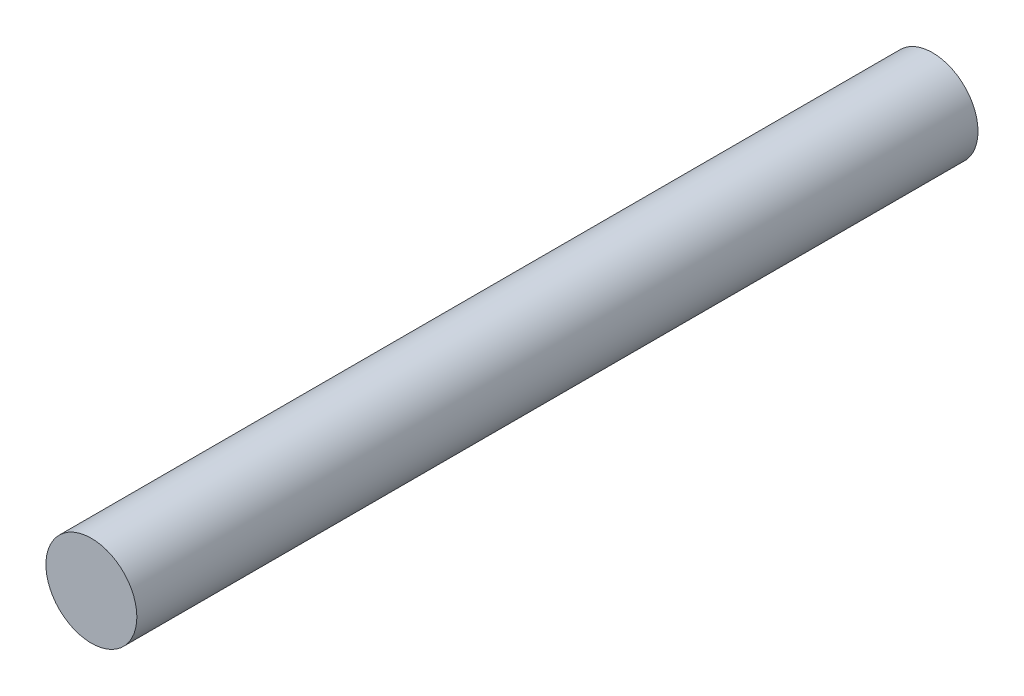
SolidWorks part; units mm, degrees
ref_plane "Front Plane" through (0, 0, 0) normal (1, 0, 0) x (0, 1, 0)
ref_plane "Top Plane" through (0, 0, 0) normal (0, 0, 1) x (0, 1, 0)
ref_plane "Right Plane" through (0, 0, 0) normal (0, 1, 0) x (-1, 0, 0)
sketch "Sketch1" plane through (0, 0, 0) normal (0, 0, 1) x (0, 1, 0)
  circle A0 centre (0, 0) radius 5
  dimension "D1" = 10
extrude "Boss-Extrude1" add sketch "Sketch1" along normal blind 92.5
